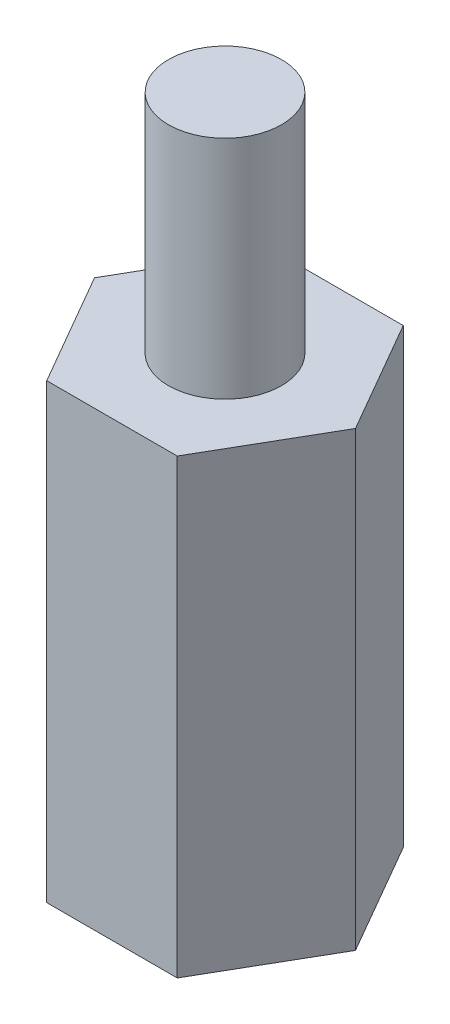
SolidWorks part; units mm, degrees
material "Brass"
ref_plane "Front Plane" through (0, 0, 0) normal (0, 0, 1) x (1, 0, 0)
ref_plane "Top Plane" through (0, 0, 0) normal (0, 1, 0) x (1, 0, 0)
ref_plane "Right Plane" through (0, 0, 0) normal (1, 0, 0) x (0, 0, -1)
sketch "Sketch1" plane through (0, 0, 0) normal (0, 1, 0) x (1, 0, 0)
  line L1 (2.8868, 0) -> (1.4434, 2.5)
  line L2 (1.4434, 2.5) -> (-1.4434, 2.5)
  line L3 (-1.4434, 2.5) -> (-2.8868, 0)
  line L4 (-2.8868, 0) -> (-1.4434, -2.5)
  line L5 (-1.4434, -2.5) -> (1.4434, -2.5)
  line L6 (1.4434, -2.5) -> (2.8868, 0)
  circle A0 centre (0, 0) radius 2.5 construction
  dimension "D1" = 5
extrude "Hex" add sketch "Sketch1" along normal blind 10
hole_wizard "M3x1.0 Female Threads" positions "Sketch4" profile "Sketch3" tap size "M3x0.5" standard "Ansi Metric"
sketch "Sketch4" plane through (0, 0, 0) normal (0, -1, 0) x (1, 0, 0)
  point P0 (0, 0)
sketch "Sketch3" plane through (0, 0, 0) normal (1, 0, 0) x (0, 0, -1)
  line L0 (0, 0) -> (0, 8.2511)
  line L1 (0, 8.2511) -> (1.25, 7.5)
  line L2 (1.25, 7.5) -> (1.25, 0)
  line L5 (1.25, 0) -> (0, 0)
  line L10 (0, 8.2511) -> (-1.25, 7.5) construction
  line L11 (0, -6.35) -> (0, 107.95) construction
  dimension "Tap Drill Dia." = 2.5
  dimension "Tap Drill Depth" = 7.5
  dimension "Drill Angle" = 118
cosmetic thread "Hole Thread1" parameters "D1"=6, "D2"=3
sketch "Sketch2" plane through (0, 10, 0) normal (0, 1, 0) x (-1, 0, 0)
  circle A0 centre (0, 0) radius 1.25
  circle A1 centre (0, 0) radius 1.25 construction
extrude "M3x1.0 Male Threads" add sketch "Sketch2" along normal blind 5
